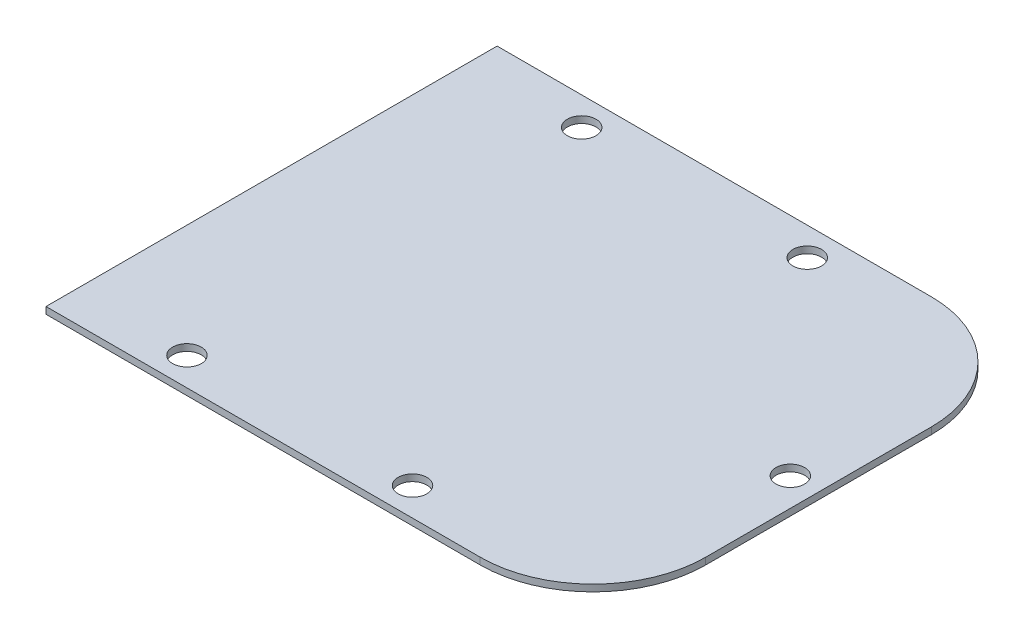
SolidWorks part; units mm, degrees
material "Acrylic (Medium-high impact)"
ref_plane "Front Plane" through (0, 0, 0) normal (0, 0, 1) x (1, 0, 0)
ref_plane "Top Plane" through (0, 0, 0) normal (0, 1, 0) x (1, 0, 0)
ref_plane "Right Plane" through (0, 0, 0) normal (1, 0, 0) x (0, 0, -1)
sketch "Sketch1" plane through (0, 0, 0) normal (0, 1, 0) x (1, 0, 0)
  line L1 (-15.3988, -12.7) -> (15.3987, -12.7)
  line L2 (-15.3988, -12.7) -> (-15.3988, 12.7)
  line L3 (-15.3988, 12.7) -> (15.3987, 12.7)
  line L4 (15.3987, -12.7) -> (15.3987, 12.7)
  line L5 (-15.3988, -12.7) -> (15.3987, 12.7) construction
  line L6 (-15.3988, 12.7) -> (15.3987, -12.7) construction
  point P0 (0, 0)
  dimension "D1" = 30.7975
  dimension "D2" = 25.4
extrude "Boss-Extrude1" add sketch "Sketch1" along normal blind 0.381
fillet "Fillet1" radius 6.35 2 edges at (15.3987, 0.1905, -12.7) (15.3987, 0.1905, 12.7)
sketch "Sketch2" plane through (0, 0.381, 0) normal (0, 1, 0) x (1, 0, 0)
  line L8 (13.8112, -6.35) -> (13.8112, 6.35)
  line L9 (9.0487, 11.1125) -> (-13.8113, 11.1125)
  line L10 (-13.8113, 11.1125) -> (-13.8113, -11.1125)
  line L11 (-13.8113, -11.1125) -> (9.0487, -11.1125)
  line L12 (13.8112, -6.35) -> (13.8112, 6.35) construction
  line L13 (9.0487, 11.1125) -> (-13.8113, 11.1125) construction
  line L14 (-13.8113, 11.1125) -> (-13.8113, -11.1125) construction
  line L15 (-13.8113, -11.1125) -> (9.0487, -11.1125) construction
  arc A4 (13.8112, 6.35) -> (9.0487, 11.1125) centre (9.0487, 6.35) ccw
  arc A5 (9.0487, -11.1125) -> (13.8112, -6.35) centre (9.0487, -6.35) ccw
  arc A6 (13.8112, 6.35) -> (9.0487, 11.1125) centre (9.0487, 6.35) ccw construction
  arc A7 (9.0487, -11.1125) -> (13.8112, -6.35) centre (9.0487, -6.35) ccw construction
  dimension "D1" = 1.5875
hole_wizard "#0 Clearance Hole1" positions "Sketch4" profile "Sketch3" hole size "#0" standard "Ansi Inch"
sketch "Sketch4" plane through (0, 0.381, 0) normal (0, 1, 0) x (-1, 0, 0)
  line L0 (-13.8112, 6.35) -> (-13.8112, -6.35) construction
  line L1 (13.8113, 11.1125) -> (-9.0487, 11.1125) construction
  line L2 (-9.0487, -11.1125) -> (13.8113, -11.1125) construction
  line L3 (15.3988, -12.7) -> (15.3988, 12.7) construction
  point P0 (9.0488, -11.1125)
  point P1 (-3.6512, -11.1125)
  point P3 (-13.8112, 0)
  point P7 (9.0488, 11.1125)
  point P11 (-3.6512, 11.1125)
  dimension "D1" = 6.35
  dimension "D2" = 12.7
sketch "Sketch3" plane through (-9.0488, 0.381, -11.1125) normal (1, 0, 0) x (0, 0, 1)
  line L0 (0, 0) -> (0, 25.8846)
  line L1 (0, 25.8846) -> (0.8064, 25.4)
  line L2 (0.8064, 25.4) -> (0.8064, 0)
  line L5 (0.8064, 0) -> (0, 0)
  line L10 (0, 25.8846) -> (-0.8065, 25.4) construction
  line L11 (0, -6.35) -> (0, 107.95) construction
  dimension "Hole Dia." = 1.6129
  dimension "Hole Depth" = 25.4
  dimension "Drill Angle" = 118
